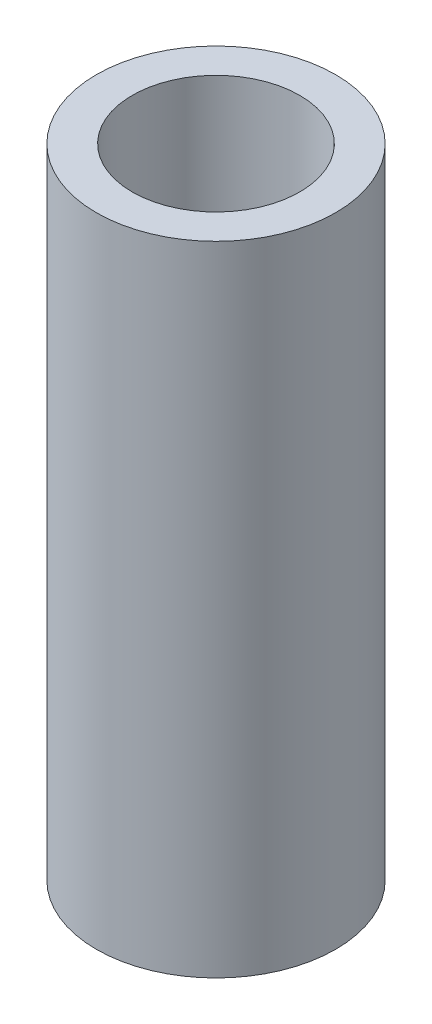
SolidWorks part; units mm, degrees
ref_plane "Front" through (0, 0, 0) normal (0, 0, 1) x (1, 0, 0)
ref_plane "Top" through (0, 0, 0) normal (0, 1, 0) x (1, 0, 0)
ref_plane "Right" through (0, 0, 0) normal (1, 0, 0) x (0, 0, -1)
sketch "Sketch1" plane through (0, 0, 0) normal (0, 1, 0) x (1, 0, 0)
  circle A0 centre (0, 0) radius 2.1
  circle A1 centre (0, 0) radius 3
extrude "Boss-Extrude1" add sketch "Sketch1" along normal blind 16
